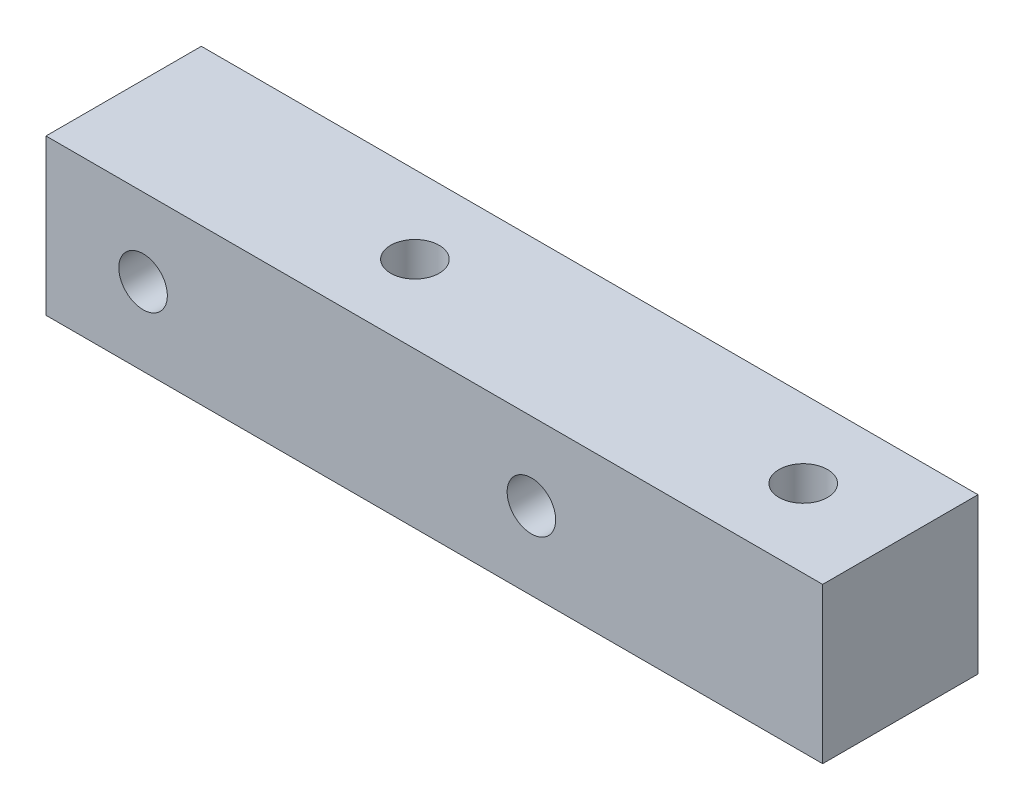
SolidWorks part; units mm, degrees
material "6061 合金"
ref_plane "前视基准面" through (0, 0, 0) normal (0, 0, 1) x (1, 0, 0)
ref_plane "上视基准面" through (0, 0, 0) normal (0, 1, 0) x (1, 0, 0)
ref_plane "右视基准面" through (0, 0, 0) normal (1, 0, 0) x (0, 0, -1)
sketch "草图1" plane through (0, 0, 0) normal (0, 0, 1) x (1, 0, 0)
  line L1 (20, -4) -> (-20, -4)
  line L2 (20, -4) -> (20, 4)
  line L3 (20, 4) -> (-20, 4)
  line L4 (-20, -4) -> (-20, 4)
  line L5 (20, -4) -> (-20, 4) construction
  line L6 (20, 4) -> (-20, -4) construction
  point P0 (0, 0)
  dimension "D1" = 40
  dimension "D2" = 8
extrude "凸台-拉伸1" add sketch "草图1" along normal blind 8
sketch "草图2" plane through (0, 0, 8) normal (0, 0, 1) x (1, 0, 0)
  line L0 (-20, 4) -> (-20, -4) construction
  point P0 (-15, 0)
  point P1 (5, 0)
  dimension "D1" = 5
  dimension "D2" = 20
sketch "草图3" plane through (0, 4, 0) normal (0, 1, 0) x (1, 0, 0)
  line L0 (20, -8) -> (20, 0) construction
  point P0 (15, -4)
  point P1 (-5, -4)
  dimension "D1" = 20
  dimension "D2" = 5
hole_wizard "M3 螺纹孔的螺纹孔钻头1" positions "3D草图1" profile "草图4" hole size "M3" standard "DIN" end condition through all
sketch3d "3D草图1"
  point P0 (-5, 4, 4)
  point P3 (15, 4, 4)
  point P6 (5, 0, 8)
  point P9 (-15, 0, 8)
sketch "草图4" plane through (-5, 4, 4) normal (1, 0, 0) x (0, 0, 1)
  line L0 (0, 0) -> (0, 8)
  line L1 (0, 8) -> (1.25, 8)
  line L2 (1.25, 8) -> (1.25, 0)
  line L5 (1.25, 0) -> (0, 0)
  line L11 (0, -6.35) -> (0, 107.95) construction
  dimension "通孔孔直径" = 2.5
  dimension "通孔孔深度" = 8
